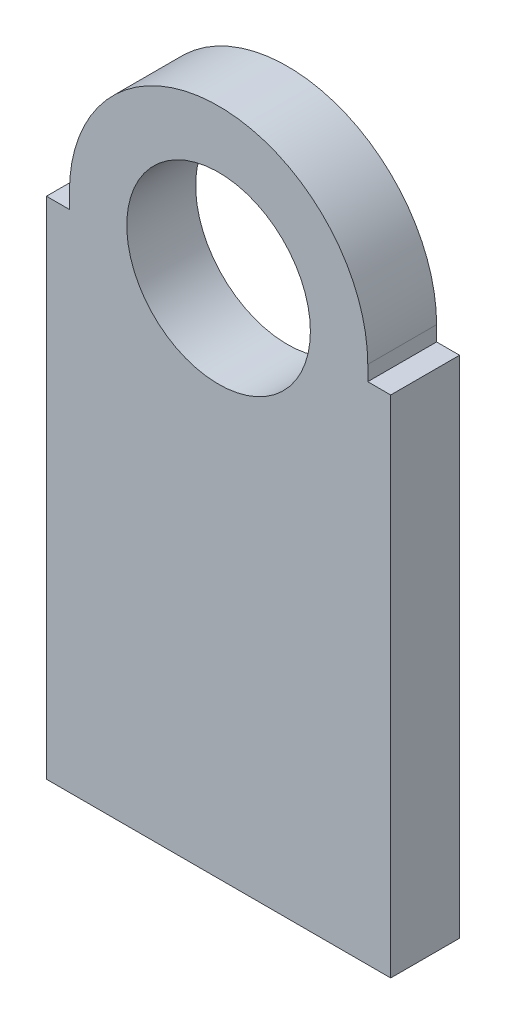
SolidWorks part; units mm, degrees
ref_plane "Front Plane" through (0, 0, 0) normal (0, 0, 1) x (1, 0, 0)
ref_plane "Top Plane" through (0, 0, 0) normal (0, 1, 0) x (1, 0, 0)
ref_plane "Right Plane" through (0, 0, 0) normal (1, 0, 0) x (0, 0, -1)
sketch "Sketch1" plane through (0, 0, 0) normal (0, 0, 1) x (1, 0, 0)
  line L0 (3.75, -1.8267) -> (3.7589, -1.8267)
  line L1 (-1.75, 3.425) -> (1.75, 3.425)
  line L2 (-3.25, 0) -> (-3.25, -0.3267)
  line L4 (3.25, 0) -> (3.25, -0.3267)
  line L5 (-1.4787, 2.8941) -> (0.9334, -1.8267) construction
  line L6 (-0.9334, -1.8267) -> (1.4787, 2.8941) construction
  line L13 (-3.75, -0.3267) -> (-3.25, -0.3267)
  line L14 (0, -55) -> (0, 55) construction
  line L15 (3.75, -0.3267) -> (3.25, -0.3267)
  line L17 (-3.75, -0.3267) -> (-3.75, -11.3267)
  line L18 (3.75, -0.3267) -> (3.75, -11.3267)
  line L19 (3.75, -11.3267) -> (-3.75, -11.3267)
  circle A0 centre (0, 0) radius 2
  circle A1 centre (0, 0) radius 3.25
  point P12 (0, -2.6767)
  dimension "D1" = 4
  dimension "D2" = 6.5
  dimension "D5" = 11
  dimension "D6" = 11
extrude "Boss-Extrude1" add sketch "Sketch1" along normal blind 1.5
